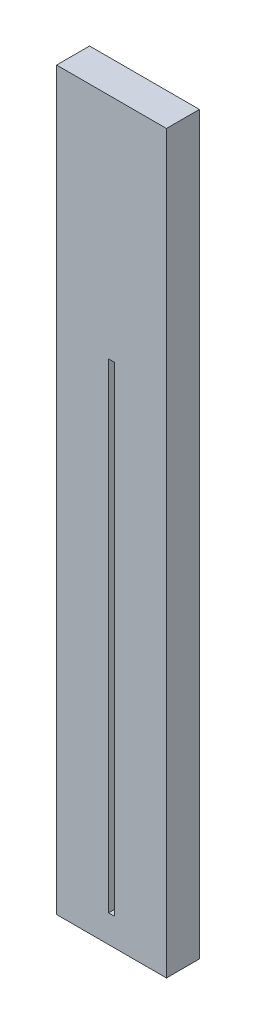
SolidWorks part; units mm, degrees
ref_plane "Front Plane" through (0, 0, 0) normal (0, 0, 1) x (1, 0, 0)
ref_plane "Top Plane" through (0, 0, 0) normal (0, 1, 0) x (1, 0, 0)
ref_plane "Right Plane" through (0, 0, 0) normal (1, 0, 0) x (0, 0, -1)
sketch "Sketch1" plane through (0, 0, 0) normal (0, 1, 0) x (1, 0, 0)
  line L1 (-56, -16.8) -> (56, -16.8)
  line L2 (-56, -16.8) -> (-56, 16.8)
  line L3 (-56, 16.8) -> (56, 16.8)
  line L4 (56, -16.8) -> (56, 16.8)
  line L5 (-56, -16.8) -> (56, 16.8) construction
  line L6 (-56, 16.8) -> (56, -16.8) construction
  point P0 (0, 0)
  dimension "D1" = 33.6
  dimension "D2" = 112
extrude "Boss-Extrude1" add sketch "Sketch1" along normal blind 750
sketch "Sketch2" plane through (0, 0, 16.8) normal (0, 0, 1) x (1, 0, 0)
  line L0 (56, 0) -> (0, 0) construction
  line L1 (0, 0) -> (0, 28) construction
  line L2 (-3.05, 28) -> (3.05, 28)
  line L3 (-3.05, 28) -> (-3.05, 517.1)
  line L4 (3.05, 28) -> (3.05, 517.1)
  line L5 (3.05, 517.1) -> (-3.05, 517.1)
  point P8 (0, 28)
  dimension "D1" = 6.1
extrude "Cut-Extrude1" cut sketch "Sketch2" against normal blind 10.1
